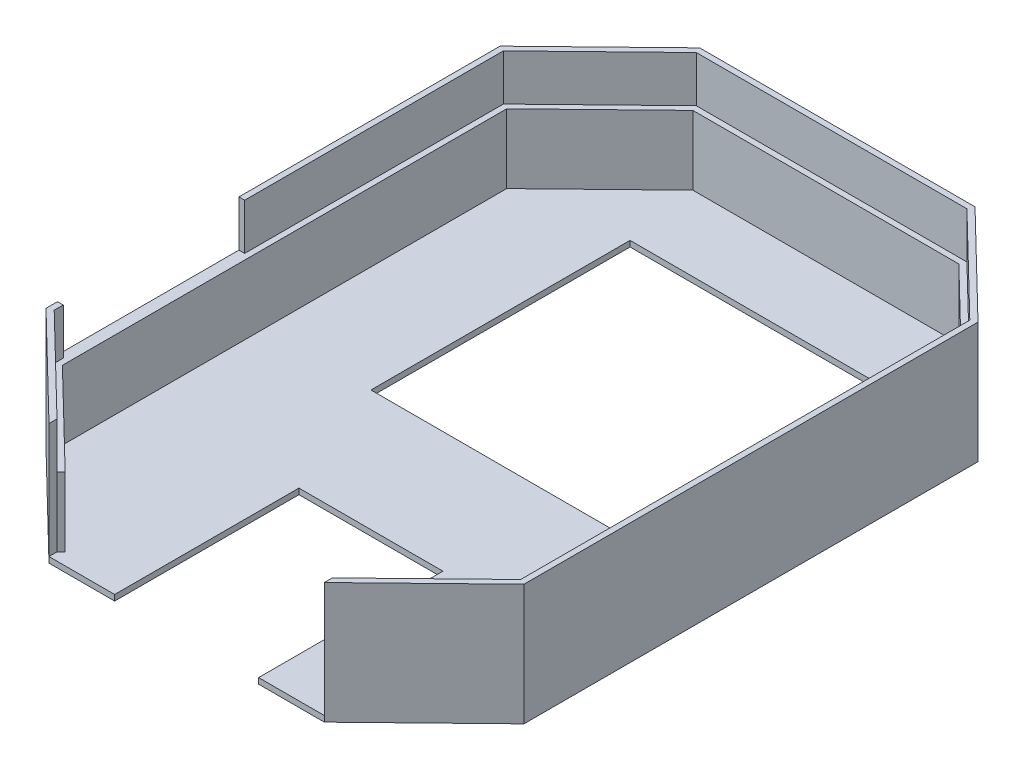
SolidWorks part; units mm, degrees
ref_plane "Alzado" through (0, 0, 0) normal (0, 0, 1) x (1, 0, 0)
ref_plane "Planta" through (0, 0, 0) normal (0, 1, 0) x (1, 0, 0)
ref_plane "Vista lateral" through (0, 0, 0) normal (1, 0, 0) x (0, 0, -1)
sketch "Croquis1" plane through (0, 0, 0) normal (0, 1, 0) x (1, 0, 0)
  line L0 (0, 0) -> (81, 0)
  line L1 (81, 0) -> (81, 111)
  line L2 (81, 111) -> (0, 111)
  line L3 (0, 111) -> (0, 0)
  line L4 (40.5, 111) -> (40.5, 0) construction
  line L5 (64, 111) -> (81, 94.5)
  line L6 (0, 55.5) -> (81, 55.5) construction
  line L7 (17, 111) -> (0, 94.5)
  line L8 (64, 0) -> (81, 16.5)
  line L9 (17, 0) -> (0, 16.5)
  dimension "D1" = 81
  dimension "D2" = 111
  dimension "D3" = 23.5
  dimension "D4" = 39
extrude "Saliente-Extruir1" add sketch "Croquis1" along normal blind 20 contours L9 L0 L8 L1 L5 L2 L7 L3
shell "Vaciado1" thickness 1
sketch "Croquis2" plane through (0, 0, 1) normal (0, 0, 1) x (1, 0, 0)
  line L0 (17, 0) -> (0, 0) construction
  line L2 (16.5945, 20) -> (16.5945, -1) construction
  line L9 (16.5945, 20) -> (16.5945, 0)
  line L10 (64, 0) -> (81, 0) construction
  line L14 (16.5945, 20) -> (64.4055, 20)
  line L15 (64.4055, 20) -> (64.4055, 0)
  line L16 (64.4055, 20) -> (64.4055, -1) construction
  line L17 (16.5945, 0) -> (64.4055, 0)
extrude "Cortar-Extruir1" cut sketch "Croquis2" against normal up to next
sketch "Croquis10" plane through (0, 0, 0) normal (0, 1, 0) x (1, 0, 0)
  line L0 (53, -1) -> (53, 31)
  line L1 (16.5945, -1) -> (64.4055, -1) construction
  line L2 (53, 31) -> (28, 31)
  line L3 (28, 31) -> (28, -1)
  line L4 (28, -1) -> (53, -1)
  line L5 (40.5, 111) -> (40.5, 0) construction
  dimension "D1" = 32
  dimension "D2" = 25
  dimension "D3" = 12.5
extrude "Cortar-Extruir7" cut sketch "Croquis10" against normal up to next
sketch "Croquis11" plane through (-1, 0, 0) normal (-1, 0, 0) x (0, 0, 1)
  line L0 (-16.077, 20) -> (-16.077, 12)
  line L1 (-16.077, 20) -> (-16.077, -1) construction
  line L2 (-16.077, 12) -> (-49.577, 12)
  line L3 (-49.577, 12) -> (-49.577, 20)
  line L4 (-94.923, 20) -> (-16.077, 20) construction
  line L5 (-49.577, 20) -> (-16.077, 20)
  line L6 (-18.077, 20) -> (-18.077, 8.7484)
  dimension "D1" = 33.5
  dimension "D2" = 8
  dimension "D3" = 2
extrude "Cortar-Extruir8" cut sketch "Croquis11" against normal up to next contours L6 L5 L3 L2
sketch "Croquis12" plane through (0, 0, 0) normal (0, 1, 0) x (1, 0, 0)
  line L0 (16.5945, 0.3936) -> (0, 16.5)
  line L1 (0, 16.5) -> (0, 94.5)
  line L2 (0, 94.5) -> (17, 111)
  line L3 (17, 111) -> (64, 111)
  line L4 (64, 111) -> (81, 94.5)
  line L5 (81, 94.5) -> (81, 16.5)
  line L6 (81, 16.5) -> (64.4055, 0.3936)
  line L7 (64.4055, 0.3936) -> (63.709, 1.1112)
  line L8 (63.709, 1.1112) -> (80, 16.923)
  line L9 (80, 94.077) -> (80, 16.923)
  line L10 (17.4055, 110) -> (63.5945, 110)
  line L11 (1, 94.077) -> (1, 16.923)
  line L12 (17.4055, 110) -> (1, 94.077)
  line L13 (63.5945, 110) -> (80, 94.077)
  line L14 (1, 16.923) -> (17.291, 1.1112)
  line L15 (16.5945, 0.3936) -> (17.291, 1.1112)
  point P18 (17.4055, 1.1112)
  point P21 (1, 19.0929)
  line M23 (64.4055, 0.3936) -> (81, 16.5)
  line M24 (81, 16.5) -> (81, 94.5)
  line M25 (81, 94.5) -> (64, 111)
  line M26 (64, 111) -> (17, 111)
  line M27 (17, 111) -> (0, 94.5)
  line M28 (0, 94.5) -> (0, 16.5)
  line M29 (0, 16.5) -> (16.5945, 0.3936)
  dimension "D1" = 1
  dimension "D2" = 1
  dimension "D3" = 1
  dimension "D4" = 1
  dimension "D5" = 1
  dimension "D6" = 1
  dimension "D7" = 1
extrude "Saliente-Extruir2" add sketch "Croquis12" along normal up to vertex contours L15 L14 L11 L12 L10 L13 L9 L8 L7 M29 M23 M24 M25 M26 M27 M28
sketch "Croquis13" plane through (0, -1, 0) normal (0, -1, 0) x (1, 0, 0)
  line L0 (-1, -52) -> (82, -52) construction
  line L1 (-1, -94.923) -> (-1, -16.077) construction
  line L2 (82, -16.077) -> (82, -94.923) construction
  line L3 (40.5, -111) -> (40.5, 0) construction
  line L4 (-1, -97) -> (82, -97) construction
  line L5 (64.4055, -112) -> (16.5945, -112) construction
  line L6 (19.5, 1) -> (19.5, -112) construction
  line L7 (16.5945, 1) -> (28, 1) construction
  line L8 (61.5, 1) -> (61.5, -112) construction
  line L9 (53, 1) -> (64.4055, 1) construction
  line L10 (61.5, -52) -> (61.5, -97)
  line L11 (61.5, -97) -> (19.5, -97)
  line L12 (19.5, -97) -> (19.5, -52)
  line L13 (19.5, -52) -> (61.5, -52)
  dimension "D1" = 60
  dimension "D2" = 42
  dimension "D3" = 21
  dimension "D4" = 15
extrude "Cortar-Extruir9" cut sketch "Croquis13" against normal up to next
